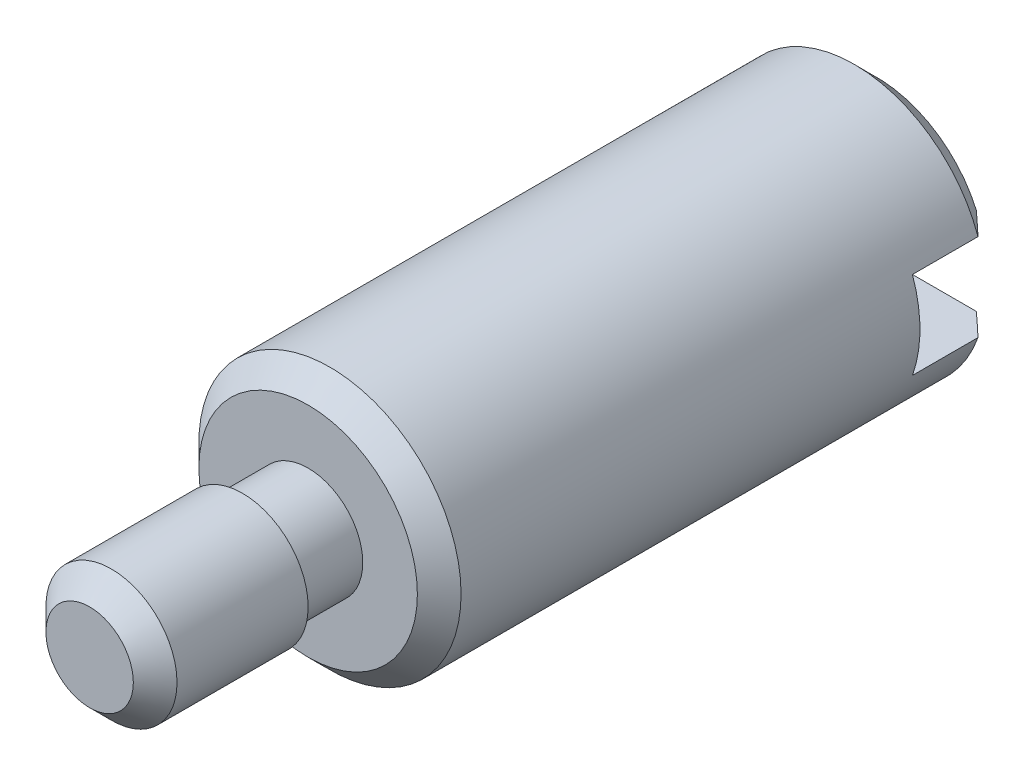
SolidWorks part; units mm, degrees
material "AISI 304"
ref_plane "前视基准面" through (0, 0, 0) normal (0, 0, 1) x (1, 0, 0)
ref_plane "上视基准面" through (0, 0, 0) normal (0, 1, 0) x (1, 0, 0)
ref_plane "右视基准面" through (0, 0, 0) normal (1, 0, 0) x (0, 0, -1)
sketch "草图1" plane through (0, 0, 0) normal (0, 0, 1) x (1, 0, 0)
  circle A0 centre (0, 0) radius 3
  dimension "D1" = 6
extrude "拉伸1" add sketch "草图1" along normal blind 13
sketch "草图2" plane through (0, 0, 13) normal (0, 0, 1) x (1, 0, 0)
  circle A0 centre (0, 0) radius 1.5
  dimension "D1" = 3
extrude "拉伸2" add sketch "草图2" along normal blind 5
cosmetic thread "装饰螺纹线1" parameters "D2"=2.5
chamfer "倒角1" distance 0.5 angle 45 1 edges at (1.5, 0, 18)
sketch "草图3" plane through (0, 0, 13) normal (0, 0, 1) x (1, 0, 0)
  circle A0 centre (0, 0) radius 1.25
  circle A1 centre (0, 0) radius 1.5 construction
  circle A2 centre (0, 0) radius 1.5
  dimension "D1" = 2.5
extrude "拉伸3" cut sketch "草图3" along normal blind 1.5
sketch "草图4" plane through (0, 0, 0) normal (1, 0, 0) x (0, 0, -1)
  line L0 (0, -3) -> (0, 3) construction
  line L1 (0, 1) -> (-2, 1)
  line L2 (0, 1) -> (0, -1)
  line L3 (0, -1) -> (-2, -1)
  line L4 (-2, 1) -> (-2, -1)
  line L5 (0, 0) -> (-2, 0) construction
  dimension "D1" = 2
  dimension "D2" = 2
extrude "拉伸4" cut sketch "草图4" against normal mid plane 20
chamfer "倒角2" distance 0.5 angle 45 3 edges at (3, 0, 13) (0, -3, 0) (0, 3, 0)
